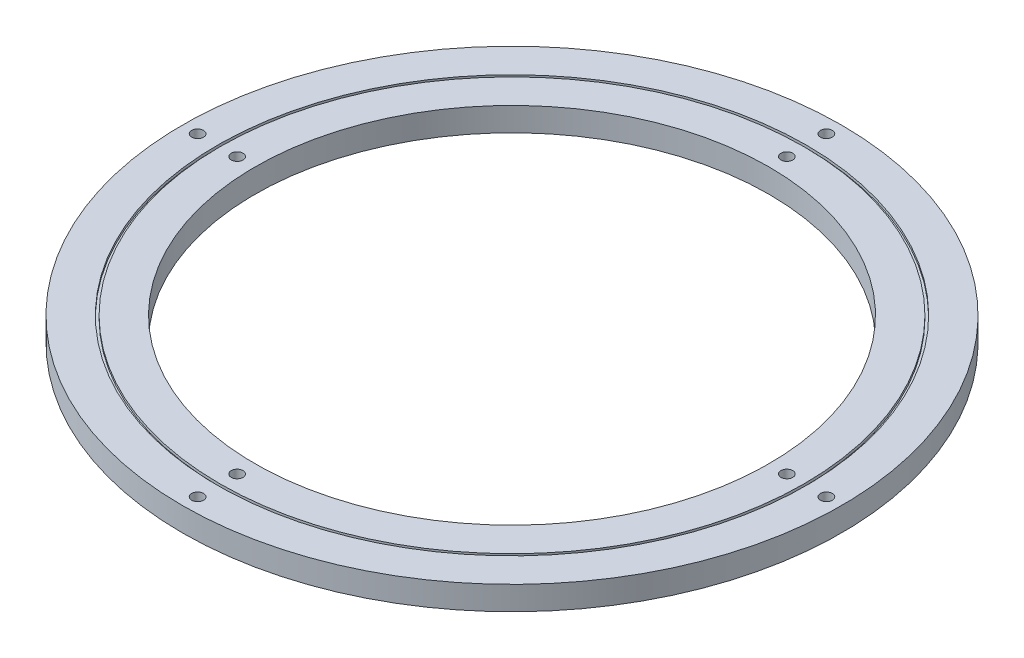
SolidWorks part; units mm, degrees
ref_plane "Front Plane" through (0, 0, 0) normal (0, 0, 1) x (1, 0, 0)
ref_plane "Top Plane" through (0, 0, 0) normal (0, 1, 0) x (1, 0, 0)
ref_plane "Right Plane" through (0, 0, 0) normal (1, 0, 0) x (0, 0, -1)
sketch "Sketch1" plane through (0, 0, 0) normal (0, 0, 1) x (1, 0, 0)
  line L0 (-97.5, -4.5) -> (-97.5, 4.5)
  line L1 (-97.5, 4.5) -> (-110.75, 4.5)
  line L2 (-110.75, 4.5) -> (-110.75, 3.5)
  line L3 (-110.75, 3.5) -> (-111.75, 3.5)
  line L4 (-111.75, 3.5) -> (-111.75, 4.5)
  line L5 (-111.75, 4.5) -> (-125, 4.5)
  line L6 (-125, 4.5) -> (-125, -4.5)
  line L7 (-125, 0) -> (-97.5, 0) construction
  line L8 (0, 0) -> (0, 128.5714) construction
  line L9 (-97.5, -4.5) -> (-110.75, -4.5)
  line L10 (-110.75, -4.5) -> (-110.75, -3.5)
  line L11 (-111.75, -3.5) -> (-111.75, -4.5)
  line L12 (-110.75, -3.5) -> (-111.75, -3.5)
  line L13 (-111.75, -4.5) -> (-125, -4.5)
  dimension "D1" = 195
  dimension "D2" = 9
  dimension "D3" = 1
  dimension "D4" = 1
  dimension "D5" = 250
revolve "Revolve1" add sketch "Sketch1" angle 360 about L8
hole_wizard "CSK for M4 Flat Head Machine Screw1" positions "Sketch2" profile "Sketch3" countersink size "M4" standard "ANSI Metric" end condition through all
sketch "Sketch2" plane through (0, -4.5, 0) normal (0, -1, 0) x (-1, 0, 0)
  circle A0 centre (0, 0) radius 104.25 construction
  circle A1 centre (0, 0) radius 119.25 construction
  point P12 (0, 104.25)
  point P14 (0, 119.25)
  point P21 (104.25, 0)
  point P22 (119.25, 0)
  point P23 (0, -104.25)
  point P24 (0, -119.25)
  point P25 (-104.25, 0)
  point P26 (-119.25, 0)
  dimension "D1" = 208.5
  dimension "D2" = 238.5
  dimension "D3" = 4
sketch "Sketch3" plane through (119.25, -4.5, 0) normal (1, 0, 0) x (0, 0, -1)
  line L0 (0, 0) -> (0, 9)
  line L1 (0, 9) -> (2.25, 9)
  line L2 (2.25, 9) -> (2.25, 2.45)
  line L3 (2.25, 2.45) -> (4.7, 0)
  line L5 (4.7, 0) -> (0, 0)
  line L6 (-2.25, 2.45) -> (-4.7, 0) construction
  line L11 (0, -6.35) -> (0, 107.95) construction
  dimension "Thru Hole Dia." = 4.5
  dimension "Thru Hole Depth" = 9
  dimension "Near C'Sink Dia." = 9.4
  dimension "Near C'Sink Angle" = 90
